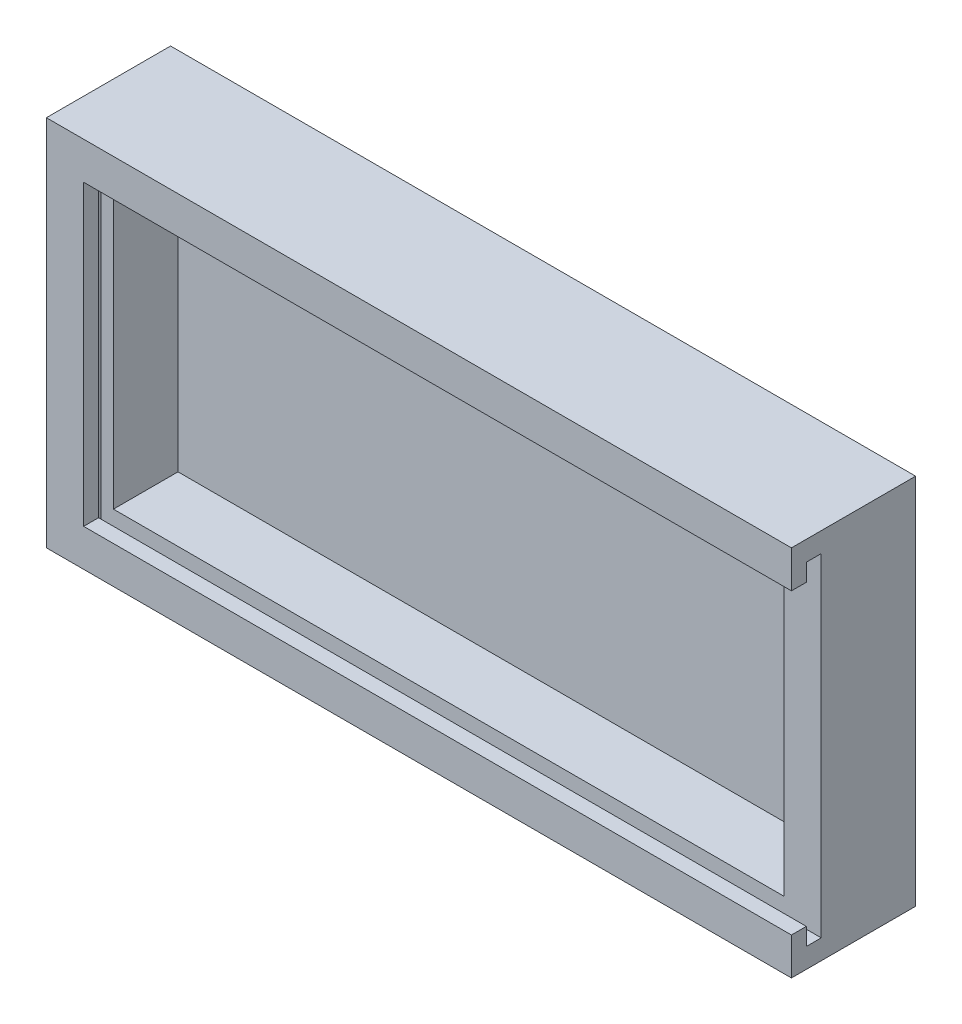
SolidWorks part; units mm, degrees
ref_plane "Front Plane" through (0, 0, 0) normal (0, 0, 1) x (1, 0, 0)
ref_plane "Top Plane" through (0, 0, 0) normal (0, 1, 0) x (1, 0, 0)
ref_plane "Right Plane" through (0, 0, 0) normal (1, 0, 0) x (0, 0, -1)
sketch "Sketch1" plane through (0, 0, 0) normal (0, 0, 1) x (1, 0, 0)
  line L1 (0, 0) -> (76.2, 0)
  line L2 (0, 0) -> (0, 38.1)
  line L3 (0, 38.1) -> (76.2, 38.1)
  line L4 (76.2, 0) -> (76.2, 38.1)
  dimension "D1" = 76.2
  dimension "D2" = 38.1
extrude "Boss-Extrude1" add sketch "Sketch1" along normal blind 12.7
sketch "Sketch3" plane through (0, 0, 12.7) normal (0, 0, 1) x (1, 0, 0)
  line L0 (38.1, 38.1) -> (38.1, 0)
  line L1 (76.2, 38.1) -> (0, 38.1) construction
  line L2 (0, 0) -> (76.2, 0) construction
  line L3 (0, 38.1) -> (0, 0) construction
  line L4 (3.81, 3.81) -> (72.39, 3.81)
  line L5 (3.81, 3.81) -> (3.81, 34.29)
  line L6 (3.81, 34.29) -> (72.39, 34.29)
  line L7 (72.39, 3.81) -> (72.39, 34.29)
  line L8 (3.81, 3.81) -> (72.39, 34.29) construction
  line L9 (3.81, 34.29) -> (72.39, 3.81) construction
  point P6 (38.1, 19.05)
  dimension "D1" = 3.81
  dimension "D2" = 3.81
extrude "Cut-Extrude1" cut sketch "Sketch3" against normal blind 9.652 contours L6 L5 L4 L0 | L4 L7 L6 L0
sketch "Sketch5" plane through (76.2, 0, 0) normal (1, 0, 0) x (0, 0, -1)
  line L0 (-12.7, 0) -> (-12.7, 38.1) construction
  line L1 (-12.7, 34.29) -> (-10.16, 34.29)
  line L2 (-12.7, 34.29) -> (-12.7, 3.81)
  line L3 (-12.7, 3.81) -> (-10.16, 3.81)
  line L4 (-10.16, 34.29) -> (-10.16, 3.81)
  line L5 (-12.7, 38.1) -> (0, 38.1) construction
  line L6 (-12.7, 0) -> (0, 0) construction
  dimension "D1" = 3.81
  dimension "D2" = 3.81
  dimension "D3" = 2.54
extrude "Cut-Extrude3" cut sketch "Sketch5" against normal up to vertex (3.81 mm away)
sketch "Sketch6" plane through (76.2, 0, 0) normal (1, 0, 0) x (0, 0, -1)
  line L0 (-12.7, 0) -> (-12.7, 3.81) construction
  line L1 (-11.176, 2.032) -> (-9.652, 2.032)
  line L2 (-11.176, 2.032) -> (-11.176, 36.068)
  line L3 (-11.176, 36.068) -> (-9.652, 36.068)
  line L4 (-9.652, 2.032) -> (-9.652, 36.068)
  line L7 (-12.7, 0) -> (0, 0) construction
  line L9 (-12.7, 38.1) -> (0, 38.1) construction
  dimension "D1" = 2.032
  dimension "D2" = 1.524
  dimension "D3" = 1.524
  dimension "D4" = 2.032
extrude "Cut-Extrude4" cut sketch "Sketch6" against normal blind 73.66
